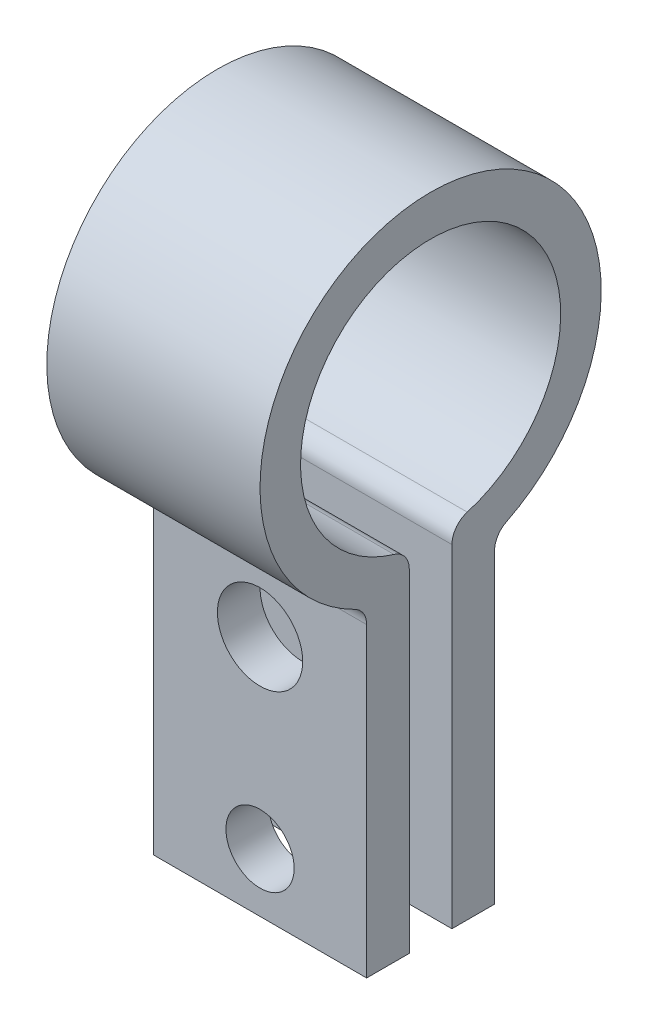
SolidWorks part; units mm, degrees
ref_plane "Front Plane" through (0, 0, 0) normal (0, 0, 1) x (1, 0, 0)
ref_plane "Top Plane" through (0, 0, 0) normal (0, 1, 0) x (1, 0, 0)
ref_plane "Right Plane" through (0, 0, 0) normal (1, 0, 0) x (0, 0, -1)
sketch "Sketch1" plane through (0, 0, 0) normal (1, 0, 0) x (0, 0, -1)
  line L0 (-3, -7.4162) -> (-3, -22.4162)
  line L1 (-3, -22.4162) -> (-1, -22.4162)
  line L2 (-1, -22.4162) -> (-1, -6.0175)
  line L3 (3, -7.4162) -> (3, -22.4162)
  line L4 (3, -22.4162) -> (1, -22.4162)
  line L5 (1, -22.4162) -> (1, -6.0175)
  line L6 (-1, -6.0175) -> (1, -6.0175) construction
  circle A0 centre (0, 0) radius 6.1 construction
  circle A1 centre (0, 0) radius 8 construction
  arc A2 (-1, -6.0175) -> (1, -6.0175) centre (0, 0) cw
  arc A3 (-3, -7.4162) -> (3, -7.4162) centre (0, 0) cw
  dimension "D1" = 12.2
  dimension "D2" = 16
  dimension "D3" = 2
  dimension "D4" = 2
  dimension "D5" = 15
extrude "Boss-Extrude1" add sketch "Sketch1" along normal mid plane 10
fillet "Fillet1" radius 1 4 edges at (0, -6.0175, 1) (0, -6.0175, -1) (0, -7.4162, 3) (0, -7.4162, -3)
sketch "Sketch3" plane through (0, 0, 3) normal (0, 0, 1) x (1, 0, 0)
  line L0 (0, -44.7868) -> (0, 44.7868) construction
  line L2 (5, -22.4162) -> (-5, -22.4162) construction
  line L3 (5, -8.0623) -> (-5, -8.0623) construction
  circle A0 centre (0, -19.6662) radius 1.6
  circle A1 centre (0, -19.6662) radius 2.75 construction
  circle A2 centre (0, -11.0623) radius 2
  dimension "D1" = 3.2
  dimension "D2" = 5.5
  dimension "D3" = 4
  dimension "D4" = 3
extrude "Cut-Extrude1" cut sketch "Sketch3" against normal through all
